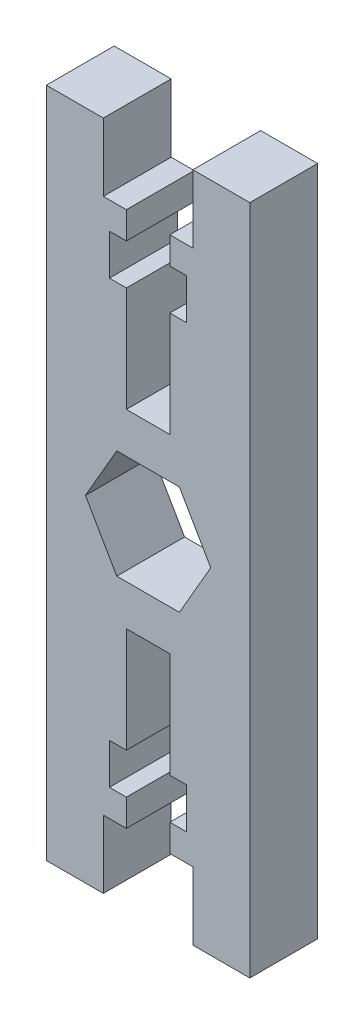
SolidWorks part; units mm, degrees
ref_plane "Plan de face" through (0, 0, 0) normal (0, 0, 1) x (1, 0, 0)
ref_plane "Plan de dessus" through (0, 0, 0) normal (0, 1, 0) x (1, 0, 0)
ref_plane "Plan de droite" through (0, 0, 0) normal (1, 0, 0) x (0, 0, -1)
sketch "Esquisse1" plane through (0, 0, 0) normal (0, 0, 1) x (1, 0, 0)
  line L0 (-12.9111, 41.3251) -> (-12.9111, -8.1749)
  line L1 (-12.9111, -8.1749) -> (-6.2111, -8.1749)
  line L2 (-6.2111, -8.1749) -> (-6.2111, -3.1749)
  line L3 (-6.2111, -3.1749) -> (-4.5111, -3.1749)
  line L4 (-4.5111, -3.1749) -> (-4.5111, -1.1782)
  line L5 (-4.5111, -1.1782) -> (-5.7611, -1.1782)
  line L6 (-5.7611, -1.1782) -> (-5.7611, 1.8218)
  line L7 (-5.7611, 1.8218) -> (-4.5111, 1.8218)
  line L8 (-4.5111, 1.8218) -> (-4.5111, 9.5751)
  line L9 (-4.5111, 9.5751) -> (-1.3111, 9.5751)
  line L10 (-1.3111, 9.5751) -> (-1.3111, 1.8218)
  line L11 (-1.3111, 1.8218) -> (-0.0611, 1.8218)
  line L12 (-0.0611, 1.8218) -> (-0.0611, -1.1782)
  line L13 (-0.0611, -1.1782) -> (-1.3111, -1.1782)
  line L14 (-1.3111, -1.1782) -> (-1.3111, -3.1749)
  line L15 (-1.3111, -3.1749) -> (0.3889, -3.1749)
  line L16 (0.3889, -3.1749) -> (0.3889, -8.1749)
  line L17 (0.3889, -8.1749) -> (7.0889, -8.1749)
  line L18 (7.0889, -8.1749) -> (7.0889, 41.3251)
  line L19 (-12.9111, 9.5751) -> (7.0889, 9.5751) construction
  line L20 (-12.9111, 16.5751) -> (7.0889, 16.5751) construction
  line L21 (-12.9111, 23.5751) -> (7.0889, 23.5751) construction
  line L22 (0.3889, 41.3251) -> (7.0889, 41.3251)
  line L23 (0.3889, 36.3251) -> (0.3889, 41.3251)
  line L24 (-1.3111, 36.3251) -> (0.3889, 36.3251)
  line L25 (-1.3111, 34.3284) -> (-1.3111, 36.3251)
  line L26 (-0.0611, 34.3284) -> (-1.3111, 34.3284)
  line L27 (-0.0611, 31.3284) -> (-0.0611, 34.3284)
  line L28 (-1.3111, 31.3284) -> (-0.0611, 31.3284)
  line L29 (-1.3111, 23.5751) -> (-1.3111, 31.3284)
  line L30 (-4.5111, 23.5751) -> (-1.3111, 23.5751)
  line L31 (-4.5111, 31.3284) -> (-4.5111, 23.5751)
  line L32 (-5.7611, 31.3284) -> (-4.5111, 31.3284)
  line L33 (-5.7611, 34.3284) -> (-5.7611, 31.3284)
  line L34 (-4.5111, 34.3284) -> (-5.7611, 34.3284)
  line L35 (-4.5111, 36.3251) -> (-4.5111, 34.3284)
  line L36 (-6.2111, 36.3251) -> (-4.5111, 36.3251)
  line L37 (-6.2111, 41.3251) -> (-6.2111, 36.3251)
  line L38 (-12.9111, 41.3251) -> (-6.2111, 41.3251)
  dimension "D1" = 24.75
  dimension "D2" = 24.75
  dimension "D3" = 20
  dimension "D4" = 6.7
  dimension "D5" = 6.7
  dimension "D6" = 3.2
  dimension "D7" = 1.7
  dimension "D8" = 7
  dimension "D9" = 3.2
  dimension "D10" = 0
  dimension "D11" = 5.7
  dimension "D12" = 1.25
  dimension "D13" = 1.9967
  dimension "D14" = 1.9967
  dimension "D15" = 3
  dimension "D16" = 3
  dimension "D17" = 5
  dimension "D18" = 5
extrude "Boss.-Extru.1" add sketch "Esquisse1" along normal blind 5
sketch "Esquisse2" plane through (0, 0, 0) normal (0, 0, -1) x (-1, 0, 0)
  line L0 (0.4111, -3.1749) -> (5.4111, -3.1749) construction
  line L1 (-15.6843, 43.0331) -> (-4.5889, 43.0331)
  line L2 (-15.6843, 43.0331) -> (-15.6843, -9.8118)
  line L3 (-15.6843, -9.8118) -> (-4.5889, -9.8118)
  line L4 (-4.5889, 43.0331) -> (-4.5889, -9.8118)
  line L5 (18.0213, 43.6732) -> (10.4111, 43.6732)
  line L6 (18.0213, 43.6732) -> (18.0213, -10.452)
  line L7 (18.0213, -10.452) -> (10.4111, -10.452)
  line L8 (10.4111, 43.6732) -> (10.4111, -10.452)
  line L11 (0.0611, 1.8218) -> (0.0611, -1.1782) construction
  dimension "D1" = 5
  dimension "D2" = 0.35
  dimension "D3" = 5
  dimension "D4" = 5
extrude "Enlèv. mat.-Extru.1" cut sketch "Esquisse2" against normal blind 10
sketch "Esquisse3" plane through (0, 0, 0) normal (0, 0, -1) x (-1, 0, 0)
  line L0 (10.4111, -8.1749) -> (10.4111, 41.3251) construction
  line L1 (5.2205, 12.5751) -> (7.5299, 16.5751)
  line L2 (7.5299, 16.5751) -> (5.2205, 20.5751)
  line L3 (5.2205, 20.5751) -> (0.6017, 20.5751)
  line L4 (0.6017, 20.5751) -> (-1.7078, 16.5751)
  line L5 (-1.7078, 16.5751) -> (0.6017, 12.5751)
  line L6 (0.6017, 12.5751) -> (5.2205, 12.5751)
  line L7 (1.3111, 23.5751) -> (4.5111, 23.5751) construction
  circle A0 centre (2.9111, 16.5751) radius 4 construction
  point P1 (0, 0)
  point P11 (10.4111, 16.5751)
  point P14 (2.9111, 23.5751)
  dimension "D1" = 8
extrude "Enlèv. mat.-Extru.2" cut sketch "Esquisse3" against normal blind 10
